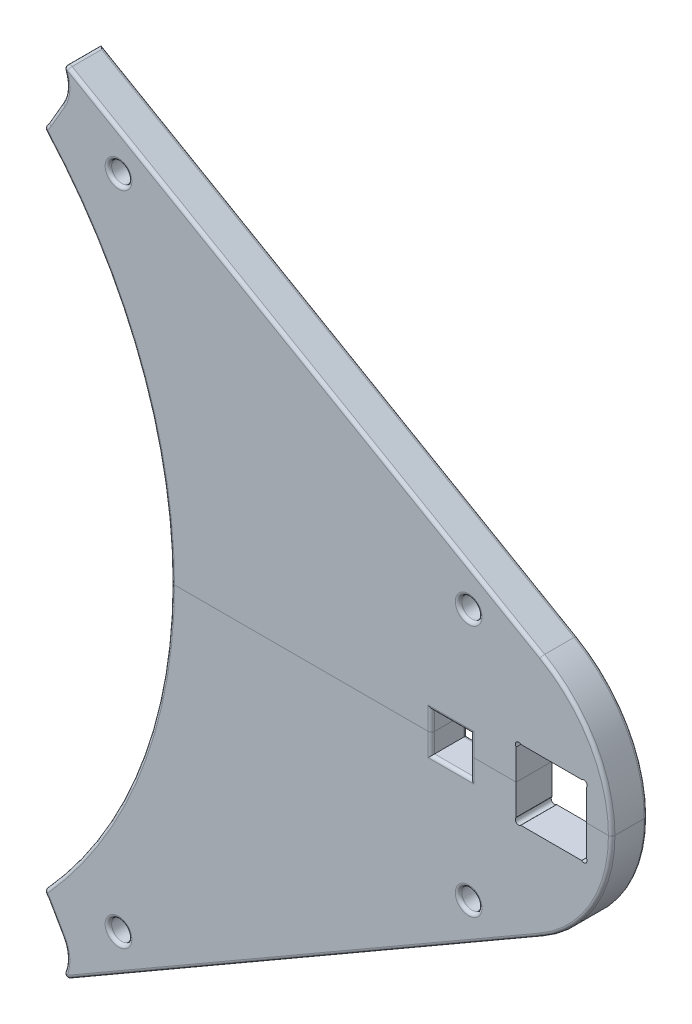
SolidWorks part; units mm, degrees
other "Side1"
other "Side2"
ref_plane "Front Plane" through (0, 0, 0) normal (0, 0, 1) x (1, 0, 0)
ref_plane "Top Plane" through (0, 0, 0) normal (0, 1, 0) x (1, 0, 0)
ref_plane "Right Plane" through (0, 0, 0) normal (1, 0, 0) x (0, 0, -1)
sketch "Sketch1" plane through (0, 0, 0) normal (0, 0, 1) x (1, 0, 0)
  line L0 (-8, 28.6603) -> (-371.7307, 238.6603) construction
  line L1 (-3, 37.3205) -> (-366.7307, 247.3205) construction
  line L2 (-13, 20) -> (-376.7307, 230) construction
  line L3 (-150.4523, 110.9051) -> (-154.6827, 103.5778) construction
  line L4 (-66.9615, 46.5359) -> (-64.9615, 50) construction
  line L5 (-66.9615, 46.5359) -> (-66.0955, 46.0359) construction
  line L6 (-64.9615, -50) -> (-66.9615, -46.5359) construction
  line L7 (-66.0955, -46.0359) -> (-66.9615, -46.5359) construction
  line L8 (-64.9615, -50) -> (-64.0955, -49.5) construction
  line L9 (-88.9, 15.5) -> (-88.9, -15.5) construction
  line L10 (-88.9, 21.15) -> (-88.9, 15.5) construction
  line L11 (-80, 21.15) -> (-88.9, 21.15) construction
  line L12 (-57, 21.05) -> (-80, 21.05) construction
  line L13 (-49.1, 21.15) -> (-57, 21.15) construction
  line L14 (-57, -21.05) -> (-80, -21.05) construction
  line L15 (-80, -21.15) -> (-88.9, -21.15) construction
  line L16 (-88.9, -15.5) -> (-88.9, -21.15) construction
  line L17 (-49.1, -21.15) -> (-57, -21.15) construction
  line L18 (-17.4535, 17.9524) -> (-15.004, 16.5382) construction
  line L19 (-15.004, -16.5382) -> (-17.4535, -17.9524) construction
  line L20 (-3.5, 36.4545) -> (-367.2307, 246.4545) construction
  line L21 (-12.5, 20.866) -> (-376.2307, 230.866) construction
  line L22 (-8, 28.6603) -> (-371.7307, 238.6603)
  line L23 (-3, 37.3205) -> (-366.7307, 247.3205)
  line L24 (-13, 20) -> (-376.7307, 230)
  line L25 (-150.4523, 110.9051) -> (-154.6827, 103.5778)
  line L26 (-66.9615, 46.5359) -> (-64.9615, 50)
  line L27 (-66.9615, 46.5359) -> (-66.0955, 46.0359)
  line L28 (-64.9615, -50) -> (-66.9615, -46.5359)
  line L29 (-66.0955, -46.0359) -> (-66.9615, -46.5359)
  line L30 (-64.9615, -50) -> (-64.0955, -49.5)
  line L31 (-88.9, 15.5) -> (-88.9, -15.5)
  line L32 (-88.9, 21.15) -> (-88.9, 15.5)
  line L33 (-80, 21.15) -> (-88.9, 21.15)
  line L34 (-57, 21.05) -> (-80, 21.05)
  line L35 (-49.1, 21.15) -> (-57, 21.15)
  line L36 (-57, -21.05) -> (-80, -21.05)
  line L37 (-80, -21.15) -> (-88.9, -21.15)
  line L38 (-88.9, -15.5) -> (-88.9, -21.15)
  line L39 (-49.1, -21.15) -> (-57, -21.15)
  line L40 (-17.4535, 17.9524) -> (-15.004, 16.5382)
  line L41 (-15.004, -16.5382) -> (-17.4535, -17.9524)
  line L42 (-3.5, 36.4545) -> (-367.2307, 246.4545)
  line L43 (-12.5, 20.866) -> (-376.2307, 230.866)
  line L44 (-37.5, 29.5263) -> (-17.4535, 17.9524) construction
  line L45 (-45, 25.1962) -> (-45, -25.1962) construction
  line L46 (-17.4535, -17.9524) -> (-37.5, -29.5263) construction
  line L47 (-37.5, 29.5263) -> (-17.4535, 17.9524)
  line L48 (-45, 25.1962) -> (-45, -25.1962)
  line L49 (-17.4535, -17.9524) -> (-37.5, -29.5263)
  line L59 (-13, 20) -> (-64.0955, 49.5)
  line L60 (-64.0955, 49.5) -> (-66.0955, 46.0359)
  line L61 (-66.0955, 46.0359) -> (-56.5, 40.4959)
  line L62 (-49, 27.5056) -> (-49, -27.5056)
  line L63 (-56.5, -40.4959) -> (-66.0955, -46.0359)
  line L64 (-66.0955, -46.0359) -> (-64.0955, -49.5)
  line L65 (-64.0955, -49.5) -> (-13, -20)
  line L66 (-13, -20) -> (-11, -23.4641)
  line L67 (-11, -23.4641) -> (-2.7728, -18.7141)
  line L68 (3.2272, -29.1064) -> (-5, -33.8564)
  line L69 (-5, -33.8564) -> (-3.5, -36.4545)
  line L70 (-3.5, 36.4545) -> (-5, 33.8564)
  line L71 (-5, 33.8564) -> (3.2272, 29.1064)
  line L72 (-2.7728, 18.7141) -> (-11, 23.4641)
  line L73 (-11, 23.4641) -> (-13, 20)
  line L74 (-13, 20) -> (-64.0955, 49.5)
  line L75 (-64.0955, 49.5) -> (-66.0955, 46.0359)
  line L76 (-66.0955, 46.0359) -> (-56.5, 40.4959)
  line L77 (-49, 27.5056) -> (-49, -27.5056)
  line L78 (-56.5, -40.4959) -> (-66.0955, -46.0359)
  line L79 (-66.0955, -46.0359) -> (-64.0955, -49.5)
  line L80 (-64.0955, -49.5) -> (-13, -20)
  line L81 (-13, -20) -> (-11, -23.4641)
  line L82 (-11, -23.4641) -> (-2.7728, -18.7141)
  line L83 (3.2272, -29.1064) -> (-5, -33.8564)
  line L84 (-5, -33.8564) -> (-3.5, -36.4545)
  line L85 (-3.5, 36.4545) -> (-5, 33.8564)
  line L86 (-5, 33.8564) -> (3.2272, 29.1064)
  line L87 (-2.7728, 18.7141) -> (-11, 23.4641)
  line L88 (-11, 23.4641) -> (-13, 20)
  line L101 (10.25, 2.75) -> (10.25, 9.567)
  line L102 (8, 2.75) -> (10.25, 2.75)
  line L103 (7.25, -2) -> (7.25, 2)
  line L104 (10.25, -2.75) -> (8, -2.75)
  line L105 (10.25, -9.567) -> (10.25, -2.75)
  line L106 (2.75, -10.25) -> (9.567, -10.25)
  line L107 (2.75, -8) -> (2.75, -10.25)
  line L108 (-2, -7.25) -> (2, -7.25)
  line L109 (-2.75, -10.25) -> (-2.75, -8)
  line L110 (-9.567, -10.25) -> (-2.75, -10.25)
  line L111 (-10.25, -2.75) -> (-10.25, -9.567)
  line L112 (-8, -2.75) -> (-10.25, -2.75)
  line L113 (-7.25, 2) -> (-7.25, -2)
  line L114 (-10.25, 2.75) -> (-8, 2.75)
  line L115 (-10.25, 9.567) -> (-10.25, 2.75)
  line L116 (-2.75, 10.25) -> (-9.567, 10.25)
  line L117 (-2.75, 8) -> (-2.75, 10.25)
  line L118 (2, 7.25) -> (-2, 7.25)
  line L119 (2.75, 10.25) -> (2.75, 8)
  line L120 (9.567, 10.25) -> (2.75, 10.25)
  line L121 (10.25, 2.75) -> (10.25, 9.567)
  line L122 (8, 2.75) -> (10.25, 2.75)
  line L123 (7.25, -2) -> (7.25, 2)
  line L124 (10.25, -2.75) -> (8, -2.75)
  line L125 (10.25, -9.567) -> (10.25, -2.75)
  line L126 (2.75, -10.25) -> (9.567, -10.25)
  line L127 (2.75, -8) -> (2.75, -10.25)
  line L128 (-2, -7.25) -> (2, -7.25)
  line L129 (-2.75, -10.25) -> (-2.75, -8)
  line L130 (-9.567, -10.25) -> (-2.75, -10.25)
  line L131 (-10.25, -2.75) -> (-10.25, -9.567)
  line L132 (-8, -2.75) -> (-10.25, -2.75)
  line L133 (-7.25, 2) -> (-7.25, -2)
  line L134 (-10.25, 2.75) -> (-8, 2.75)
  line L135 (-10.25, 9.567) -> (-10.25, 2.75)
  line L136 (-2.75, 10.25) -> (-9.567, 10.25)
  line L137 (-2.75, 8) -> (-2.75, 10.25)
  line L138 (2, 7.25) -> (-2, 7.25)
  line L139 (2.75, 10.25) -> (2.75, 8)
  line L140 (9.567, 10.25) -> (2.75, 10.25)
  arc A0 (-156.5871, 101.2051) -> (-155.3228, 102.6048) centre (-163.343, 108.5778) ccw construction
  arc A1 (-155.3228, 102.6048) -> (-154.6827, 103.5778) centre (-163.343, 108.5778) ccw construction
  arc A2 (-150.4523, 110.9051) -> (-154.1126, 124.5654) centre (-159.1126, 115.9051) ccw construction
  arc A3 (-3, -37.3205) -> (-3, 37.3205) centre (-24.547, 0) ccw construction
  arc A4 (-13.0102, 13.2963) -> (-15.004, 16.5382) centre (-17.004, 13.0741) ccw construction
  arc A5 (-15.004, -16.5382) -> (-13.0102, -13.2963) centre (-17.004, -13.0741) ccw construction
  arc A6 (-156.5871, 101.2051) -> (-155.3228, 102.6048) centre (-163.343, 108.5778) ccw
  arc A7 (-155.3228, 102.6048) -> (-154.6827, 103.5778) centre (-163.343, 108.5778) ccw
  arc A8 (-150.4523, 110.9051) -> (-154.1126, 124.5654) centre (-159.1126, 115.9051) ccw
  arc A9 (-3, -37.3205) -> (-3, 37.3205) centre (-24.547, 0) ccw
  arc A10 (-13.0102, 13.2963) -> (-15.004, 16.5382) centre (-17.004, 13.0741) ccw
  arc A11 (-15.004, -16.5382) -> (-13.0102, -13.2963) centre (-17.004, -13.0741) ccw
  circle A12 centre (-267.0341, 0) radius 150 construction
  circle A13 centre (-267.0341, 0) radius 150
  arc A14 (-37.5, 29.5263) -> (-45, 25.1962) centre (-40, 25.1962) ccw construction
  arc A15 (-45, -25.1962) -> (-37.5, -29.5263) centre (-40, -25.1962) ccw construction
  arc A16 (-13.6106, 10.9564) -> (-13.6106, -10.9564) centre (3.9461, 0) ccw construction
  arc A17 (-13.0102, -13.2963) -> (-13.6106, -10.9564) centre (-17.004, -13.0741) ccw construction
  arc A18 (-13.6106, 10.9564) -> (-13.0102, 13.2963) centre (-17.004, 13.0741) ccw construction
  arc A19 (-49, 27.5056) -> (-56.5, 40.4959) centre (-64, 27.5056) ccw
  arc A20 (-56.5, -40.4959) -> (-49, -27.5056) centre (-64, -27.5056) ccw
  arc A21 (5.4234, -20.9103) -> (-2.7728, -18.7141) centre (0.2272, -23.9103) ccw
  arc A22 (3.2272, -29.1064) -> (5.4234, -20.9103) centre (0.2272, -23.9103) ccw
  arc A23 (-3.5, -36.4545) -> (-3.5, 36.4545) centre (-24.547, 0) ccw
  arc A24 (5.4234, 20.9103) -> (3.2272, 29.1064) centre (0.2272, 23.9103) ccw
  arc A25 (-2.7728, 18.7141) -> (5.4234, 20.9103) centre (0.2272, 23.9103) ccw
  arc A26 (-49, 27.5056) -> (-56.5, 40.4959) centre (-64, 27.5056) ccw
  arc A27 (-56.5, -40.4959) -> (-49, -27.5056) centre (-64, -27.5056) ccw
  arc A28 (5.4234, -20.9103) -> (-2.7728, -18.7141) centre (0.2272, -23.9103) ccw
  arc A29 (3.2272, -29.1064) -> (5.4234, -20.9103) centre (0.2272, -23.9103) ccw
  arc A30 (-3.5, -36.4545) -> (-3.5, 36.4545) centre (-24.547, 0) ccw
  arc A31 (5.4234, 20.9103) -> (3.2272, 29.1064) centre (0.2272, 23.9103) ccw
  arc A32 (-2.7728, 18.7141) -> (5.4234, 20.9103) centre (0.2272, 23.9103) ccw
  arc A33 (-37.5, 29.5263) -> (-45, 25.1962) centre (-40, 25.1962) ccw
  arc A34 (-45, -25.1962) -> (-37.5, -29.5263) centre (-40, -25.1962) ccw
  arc A35 (-13.6106, 10.9564) -> (-13.6106, -10.9564) centre (3.9461, 0) ccw
  arc A36 (-13.0102, -13.2963) -> (-13.6106, -10.9564) centre (-17.004, -13.0741) ccw
  arc A37 (-13.6106, 10.9564) -> (-13.0102, 13.2963) centre (-17.004, 13.0741) ccw
  arc A50 (8, 2.75) -> (7.25, 2) centre (8, 2) ccw
  arc A51 (7.25, -2) -> (8, -2.75) centre (8, -2) ccw
  arc A52 (9.567, -10.25) -> (10.25, -9.567) centre (10, -10) ccw
  arc A53 (2.75, -8) -> (2, -7.25) centre (2, -8) ccw
  arc A54 (-2, -7.25) -> (-2.75, -8) centre (-2, -8) ccw
  arc A55 (-10.25, -9.567) -> (-9.567, -10.25) centre (-10, -10) ccw
  arc A56 (-8, -2.75) -> (-7.25, -2) centre (-8, -2) ccw
  arc A57 (-7.25, 2) -> (-8, 2.75) centre (-8, 2) ccw
  arc A58 (-9.567, 10.25) -> (-10.25, 9.567) centre (-10, 10) ccw
  arc A59 (-2.75, 8) -> (-2, 7.25) centre (-2, 8) ccw
  arc A60 (2, 7.25) -> (2.75, 8) centre (2, 8) ccw
  arc A61 (10.25, 9.567) -> (9.567, 10.25) centre (10, 10) ccw
  arc A62 (8, 2.75) -> (7.25, 2) centre (8, 2) ccw
  arc A63 (7.25, -2) -> (8, -2.75) centre (8, -2) ccw
  arc A64 (9.567, -10.25) -> (10.25, -9.567) centre (10, -10) ccw
  arc A65 (2.75, -8) -> (2, -7.25) centre (2, -8) ccw
  arc A66 (-2, -7.25) -> (-2.75, -8) centre (-2, -8) ccw
  arc A67 (-10.25, -9.567) -> (-9.567, -10.25) centre (-10, -10) ccw
  arc A68 (-8, -2.75) -> (-7.25, -2) centre (-8, -2) ccw
  arc A69 (-7.25, 2) -> (-8, 2.75) centre (-8, 2) ccw
  arc A70 (-9.567, 10.25) -> (-10.25, 9.567) centre (-10, 10) ccw
  arc A71 (-2.75, 8) -> (-2, 7.25) centre (-2, 8) ccw
  arc A72 (2, 7.25) -> (2.75, 8) centre (2, 8) ccw
  arc A73 (10.25, 9.567) -> (9.567, 10.25) centre (10, 10) ccw
  dimension "D1" = 0
  dimension "D2" = 0
sketch "Sketch2" plane through (0, 0, 0) normal (0, 0, 1) x (1, 0, 0)
  line L1 (-3, 37.3205) -> (-366.7307, 247.3205) construction
  line L2 (-3, 37.3205) -> (-151.3399, 122.9646)
  line L3 (10.75, 0) -> (18.547, 0)
  line L4 (-116.5341, 0) -> (-36.75, 0)
  line L5 (-36.75, 0) -> (-36.75, 6)
  line L6 (-154.2497, 103.3278) -> (-150.0193, 110.6551)
  line L7 (-154.2497, 103.3278) -> (-150.0193, 110.6551)
  line L8 (-36.75, 6) -> (-24.75, 6)
  line L9 (-24.75, 6) -> (-24.75, 0)
  line L10 (-24.75, 0) -> (-10.75, 0)
  line L49 (38.1755, 0) -> (27.1793, 0) construction
  line L60 (2, 7.75) -> (-2, 7.75)
  line L61 (8, 2.25) -> (10.75, 2.25)
  line L62 (7.75, -2) -> (7.75, 2)
  line L63 (-7.75, 2) -> (-7.75, -2)
  line L64 (-10.75, 2.25) -> (-8, 2.25)
  line L65 (10.75, 2.25) -> (10.75, 9.3386)
  line L66 (9.3386, 10.75) -> (2.25, 10.75)
  line L67 (2.25, 10.75) -> (2.25, 8)
  line L68 (-2.25, 8) -> (-2.25, 10.75)
  line L69 (-10.75, 9.3386) -> (-10.75, 2.25)
  line L70 (-2.25, 10.75) -> (-9.3386, 10.75)
  line L76 (10.75, 0) -> (10.75, 9.3386)
  line L80 (-10.75, 9.3386) -> (-10.75, 0)
  line L81 (9.3386, 10.75) -> (-9.3386, 10.75)
  arc A0 (-3, -37.3205) -> (-3, 37.3205) centre (-24.547, 0) ccw construction
  arc A1 (18.547, 0) -> (-3, 37.3205) centre (-24.547, 0) ccw
  circle A21 centre (-267.0341, 0) radius 150.5
  arc A22 (-154.9218, 102.3062) -> (-154.2497, 103.3278) centre (-163.343, 108.5778) ccw
  arc A23 (-156.2493, 100.8364) -> (-154.9218, 102.3062) centre (-163.343, 108.5778) ccw
  arc A24 (-150.0193, 110.6551) -> (-153.8626, 124.9984) centre (-159.1126, 115.9051) ccw
  arc A25 (-154.9218, 102.3062) -> (-154.2497, 103.3278) centre (-163.343, 108.5778) ccw
  arc A26 (-155.7518, 101.3237) -> (-154.9218, 102.3062) centre (-163.343, 108.5778) ccw
  arc A27 (-150.0193, 110.6551) -> (-151.3399, 122.9646) centre (-159.1126, 115.9051) ccw
  arc A28 (-116.5341, 0) -> (-155.7518, 101.3237) centre (-267.0341, 0) ccw
  arc A54 (2, 7.75) -> (2.25, 8) centre (2, 8) ccw
  arc A55 (-2.25, 8) -> (-2, 7.75) centre (-2, 8) ccw
  arc A56 (8, 2.25) -> (7.75, 2) centre (8, 2) ccw
  arc A57 (-7.75, 2) -> (-8, 2.25) centre (-8, 2) ccw
  arc A58 (10.75, 9.3386) -> (9.3386, 10.75) centre (10, 10) ccw
  arc A59 (-9.3386, 10.75) -> (-10.75, 9.3386) centre (-10, 10) ccw
  arc A64 (10.75, 9.3386) -> (9.3386, 10.75) centre (10, 10) ccw
  arc A65 (-9.3386, 10.75) -> (-10.75, 9.3386) centre (-10, 10) ccw
  dimension "D4" = 14
  dimension "D5" = 26
  dimension "D6" = 12
  dimension "D1" = 0.5
  dimension "D2" = 0.5
  dimension "D3" = 0.5
extrude "Boss-Extrude1" add sketch "Sketch2" along normal up to surface (11 mm away)
sketch "Sketch3" plane through (0, 0, 0) normal (0, 0, -1) x (-1, 0, 0)
  line L22 (45, 25.1962) -> (45, -25.1962) construction
  line L23 (49, 27.5056) -> (49, -27.5056) construction
  line L24 (66.0955, 46.0359) -> (56.5, 40.4959) construction
  line L25 (64.0955, 49.5) -> (66.0955, 46.0359) construction
  line L26 (37.5, 29.5263) -> (17.4535, 17.9524) construction
  line L27 (17.4535, 17.9524) -> (15.004, 16.5382) construction
  line L32 (13, 20) -> (376.7307, 230) construction
  line L33 (147.4212, 109.1551) -> (151.6517, 101.8278)
  line L34 (4.5, 34.7224) -> (145.6157, 116.1956)
  line L35 (8.6081, 13.75) -> (-8.6081, 13.75)
  line L36 (13.75, 3) -> (13.75, 8.6081)
  line L37 (21.75, 3) -> (13.75, 3)
  line L38 (21.75, 9) -> (21.75, 3)
  line L39 (39.75, 9) -> (21.75, 9)
  line L40 (39.75, 3) -> (39.75, 9)
  line L41 (113.5634, 3) -> (39.75, 3)
  line L42 (45, 3) -> (39.75, 3)
  line L43 (88.9, 15.5) -> (88.9, -15.5) construction
  line L46 (21.75, 3) -> (16.5302, 3)
  line L47 (21.75, 9) -> (21.75, 3)
  line L48 (39.75, 9) -> (21.75, 9)
  line L49 (39.75, 3) -> (39.75, 9)
  line L50 (49, 0) -> (91.9, 0)
  line L51 (45, 25.1962) -> (45, 3)
  line L52 (49, 27.5056) -> (49, 0)
  line L53 (66.0955, 46.0359) -> (56.5, 40.4959)
  line L54 (64.0955, 49.5) -> (66.0955, 46.0359)
  line L55 (37.5, 29.5263) -> (17.4535, 17.9524)
  line L56 (17.4535, 17.9524) -> (15.004, 16.5382)
  line L59 (116.5341, 0) -> (36.75, 0) construction
  line L60 (91.9, 0) -> (91.9, 3)
  line L61 (64.0955, 49.5) -> (149.625, 98.8805)
  line L62 (91.9, 3) -> (113.5634, 3)
  line L70 (-13.75, 3) -> (-15.4346, 3)
  line L72 (-13.75, 8.6081) -> (-13.75, 3)
  arc A11 (56.5, 40.4959) -> (49, 27.5056) centre (64, 27.5056) ccw construction
  arc A12 (45, 25.1962) -> (37.5, 29.5263) centre (40, 25.1962) ccw construction
  arc A16 (145.6157, 116.1956) -> (147.4212, 109.1551) centre (159.1126, 115.9051) ccw
  arc A17 (4.5, 34.7224) -> (-15.4346, 3) centre (24.547, 0) ccw
  arc A18 (-8.6081, 13.75) -> (-13.75, 8.6081) centre (-10, 10) ccw
  arc A19 (13.75, 8.6081) -> (8.6081, 13.75) centre (10, 10) ccw
  arc A20 (153.5335, 103.3434) -> (113.5634, 3) centre (267.0341, 0) ccw
  arc A21 (15.004, 16.5382) -> (13.0102, 13.2963) centre (17.004, 13.0741) ccw construction
  arc A22 (13.0102, 13.2963) -> (13.6106, 10.9564) centre (17.004, 13.0741) ccw construction
  arc A23 (13.6106, -10.9564) -> (13.6106, 10.9564) centre (-3.9461, 0) ccw construction
  arc A24 (15.004, 16.5382) -> (13.0102, 13.2963) centre (17.004, 13.0741) ccw
  arc A25 (149.625, 98.8805) -> (113.5634, 3) centre (267.0341, 0) ccw
  arc A26 (56.5, 40.4959) -> (49, 27.5056) centre (64, 27.5056) ccw
  arc A27 (45, 25.1962) -> (37.5, 29.5263) centre (40, 25.1962) ccw
  arc A28 (13.0102, 13.2963) -> (13.6106, 10.9564) centre (17.004, 13.0741) ccw
  arc A29 (16.5302, 3) -> (13.6106, 10.9564) centre (-3.9461, 0) ccw
  dimension "D2" = 3
  dimension "D1" = 3
extrude "Cut-Extrude1" cut sketch "Sketch3" against normal offset from surface (9 mm away) 2 up to face at (-48.1658, 31.5185, 11)
sketch "Sketch4" plane through (0, 0, 9) normal (0, 0, -1) x (-1, 0, 0)
  line L0 (91.9, 0) -> (91.9, 3) construction
  line L1 (49, 27.5056) -> (49, 0) construction
  line L2 (91.9, 0) -> (91.9, 3)
  line L3 (49, 3) -> (49, 0)
  line L4 (91.9, 3) -> (49, 3)
  line L5 (91.9, 0) -> (49, 0)
extrude "Boss-Extrude2" add sketch "Sketch4" along normal offset from surface (6 mm away) 3 up to face at (-59.2509, 31.0898, 0)
sketch "Sketch5" plane through (0, 0, 0) normal (0, 0, -1) x (-1, 0, 0)
  line L0 (8, 28.6603) -> (150.0193, 110.6551) construction
  line L1 (6.5, 31.2583) -> (148.8984, 113.4721)
  line L2 (9.5, 26.0622) -> (151.5193, 108.0571)
  line L3 (6.5, 31.2583) -> (9.5, 26.0622)
  line L8 (150.0193, 110.6551) -> (154.2497, 103.3278) construction
  line L9 (150.0193, 110.6551) -> (154.2497, 103.3278)
  arc A0 (151.3399, 122.9646) -> (150.0193, 110.6551) centre (159.1126, 115.9051) ccw construction
  arc A1 (148.8984, 113.4721) -> (150.0193, 110.6551) centre (159.1126, 115.9051) ccw
  dimension "D1" = 6
extrude "Boss-Extrude3" add sketch "Sketch5" along normal blind 2
sketch "Sketch8" plane through (0, 3, 0) normal (0, 1, 0) x (1, 0, 0)
  line L1 (-49, -9) -> (-113.5634, -9) construction
  line L2 (-91.9, 0) -> (-113.5634, 0) construction
  line L3 (-91.9, -3) -> (-91.9, 0) construction
  line L4 (-113.5634, 0) -> (-115.8044, 0)
  line L5 (-91.9, -9) -> (-115.8044, -9)
  line L6 (-91.9, 0) -> (-113.5634, 0)
  line L7 (-91.9, -9) -> (-91.9, 0)
  line L8 (-115.8044, 0) -> (-115.8044, -9)
  line L9 (-116.5341, 0) -> (-155.7518, 0) construction
extrude "Boss-Extrude5" add sketch "Sketch8" along normal blind 4
sketch "Sketch9" plane through (0, 7, 0) normal (0, 1, 0) x (1, 0, 0)
  line L0 (-113.6938, -4.5) -> (-91.9, -4.5) construction
  line L1 (-113.6938, -9) -> (-113.6938, 0) construction
  line L2 (-91.9, -9) -> (-91.9, 0) construction
  line L3 (-102.7969, -4.5) -> (-102.7969, 0) construction
  line L4 (-91.9, 0) -> (-113.6938, 0) construction
  line L5 (-91.9, -9) -> (-91.9, -3) construction
  circle A0 centre (-96.9, -4.5) radius 1.6
  circle A1 centre (-108.6938, -4.5) radius 1.6
  dimension "D1" = 3.2
  dimension "D2" = 5
extrude "Cut-Extrude3" cut sketch "Sketch9" against normal through all
sketch "Sketch12" plane through (0, 0, -2) normal (0, 0, -1) x (-1, 0, 0)
  line L0 (8, 28.6603) -> (150.0193, 110.6551) construction
  line L1 (6.5, 31.2583) -> (9.5, 26.0622) construction
  line L2 (79.0097, 69.6577) -> (82.1938, 64.1426) construction
  circle A0 centre (25.3205, 38.6603) radius 1.6
  circle A1 centre (132.6988, 100.6551) radius 1.6
  dimension "D1" = 3.2
  dimension "D2" = 20
extrude "Cut-Extrude6" cut sketch "Sketch12" against normal through all
sketch "Sketch13" plane through (0, 0, 11) normal (0, 0, 1) x (1, 0, 0)
  circle A0 centre (-132.6988, 100.6551) radius 3.1
  circle A1 centre (-25.3205, 38.6603) radius 3.1
  dimension "D1" = 6.2
extrude "Cut-Extrude7" cut sketch "Sketch13" against normal offset from surface (9 mm away) 2 up to face at (-58.915, 33.9477, 0)
fillet "Fillet1" radius 1 17 edges at (-154.9408, 102.2808, 11) (-152.1345, 106.9915, 11) (-77.17, 80.1426, 11) (-77.17, 80.1426, 0) (-155.7518, 101.3237, 5.5) (-126.6806, 54.3243, 0) (-126.6806, 54.3243, 11) (-148.6725, 117.0252, 11) (12.7735, 21.547, 11) (-151.3399, 122.9646, 5.5) (12.7735, 21.547, 0) (-24.75, 3, 0) (-24.75, 3, 11) (-30.75, 6, 11) (-30.75, 6, 0) (-36.75, 3, 0) (-36.75, 3, 11)
fillet "Fillet2" radius 1 55 edges at (-45, 14.0981, 9) (-42.375, 3, 9) (-39.75, 6, 9) (-30.75, 9, 9) (-21.75, 6, 9) (-19.1401, 3, 9) (-15.4821, 7.1293, 9) (-13.1231, 14.0429, 9) (-26.252, 23.0322, 9) (-42.5, 29.5263, 9) (-51.0096, 35.0056, 9) (-61.2977, 43.2659, 9) (-65.0955, 47.7679, 9) (-106.8603, 74.1902, 9) (-124.0767, 55.9056, 9) (-70.45, 3, 9) (-49, 15.2528, 9) (-102.7969, 7, 9) (-91.9, 5, 9) (-19.1401, 3, 0) (-49, 1.5, 3) (-124.0767, 55.9056, 0) (-45, 14.0981, 0) (-15.4821, 7.1293, 0) (-13.1231, 14.0429, 0) (-26.252, 23.0322, 0) (-61.2977, 43.2659, 0) (-51.0096, 35.0056, 0) (-149.625, 98.8805, 4.5) (-64.0955, 49.5, 4.5) (-66.0955, 46.0359, 4.5) (-21.75, 3, 4.5) (-21.75, 6, 0) (-16.5302, 3, 4.5) (-21.75, 9, 4.5) (-39.75, 9, 4.5) (-39.75, 3, 4.5) (-45, 3, 4.5) (-42.375, 3, 0) (-39.75, 6, 0) (-30.75, 9, 0) (-42.5, 29.5263, 0) (-106.8603, 74.1902, 0) (-65.0955, 47.7679, 0) (-49, 13.7528, 0) (-49, 3, 6) (-70.45, 3, 3) (-102.7969, 7, 0) (-113.6938, 7, 4.5) (-91.9, 7, 4.5) (-91.9, 3, 6) (-91.9, 1.5, 3) (-91.9, 3.5, 0) (-129.5988, 100.6551, 11) (-22.2205, 38.6603, 11)
mirror "Mirror1" about plane through (0, 0, 0) normal (0, 1, 0) of bodies 114 104
sketch "Sketch10" plane through (0, 7, 0) normal (0, 1, 0) x (1, 0, 0)
  circle A0 centre (-108.6938, -4.5) radius 2.9
  circle A1 centre (-96.9, -4.5) radius 2.9
  dimension "D1" = 5.8
extrude "Cut-Extrude4" cut sketch "Sketch10" against normal blind 2
sketch "Sketch11" plane through (0, -7, 0) normal (0, -1, 0) x (1, 0, 0)
  line L0 (-108.6938, 4.5) -> (-105.3452, 4.5) construction
  line L1 (-105.3452, 4.5) -> (-107.0195, 7.4)
  line L2 (-107.0195, 7.4) -> (-110.3681, 7.4)
  line L3 (-110.3681, 7.4) -> (-112.0424, 4.5)
  line L4 (-112.0424, 4.5) -> (-110.3681, 1.6)
  line L5 (-110.3681, 1.6) -> (-107.0195, 1.6)
  line L6 (-107.0195, 1.6) -> (-105.3452, 4.5)
  line L7 (-100.2486, 4.5) -> (-98.5743, 1.6)
  line L8 (-98.5743, 1.6) -> (-95.2257, 1.6)
  line L9 (-95.2257, 1.6) -> (-93.5514, 4.5)
  line L10 (-93.5514, 4.5) -> (-95.2257, 7.4)
  line L11 (-95.2257, 7.4) -> (-98.5743, 7.4)
  line L12 (-98.5743, 7.4) -> (-100.2486, 4.5)
  line L13 (-96.9, 4.5) -> (-100.2486, 4.5) construction
  circle A0 centre (-108.6938, 4.5) radius 2.9 construction
  circle A1 centre (-96.9, 4.5) radius 2.9 construction
  dimension "D1" = 5.8
extrude "Cut-Extrude5" cut sketch "Sketch11" against normal blind 2
delete or keep bodies "Body-Delete1" [suppressed] type delete bodies bodies 112
delete or keep bodies "Body-Delete2" [suppressed] type delete bodies bodies 111
equation "\"Spacing\"=0.5"
equation "\"D1@Sketch2\"=\"Spacing\""
equation "\"D2@Sketch2\"=\"Spacing\""
equation "\"D3@Sketch2\"=\"Spacing\""
equation "\"WallThickness\"=3"
equation "\"D2@Sketch3\"=\"WallThickness\""
equation "\"D1@Cut-Extrude1\"=\"Surfacethicknes\""
equation "\"Surfacethicknes\"=2"
